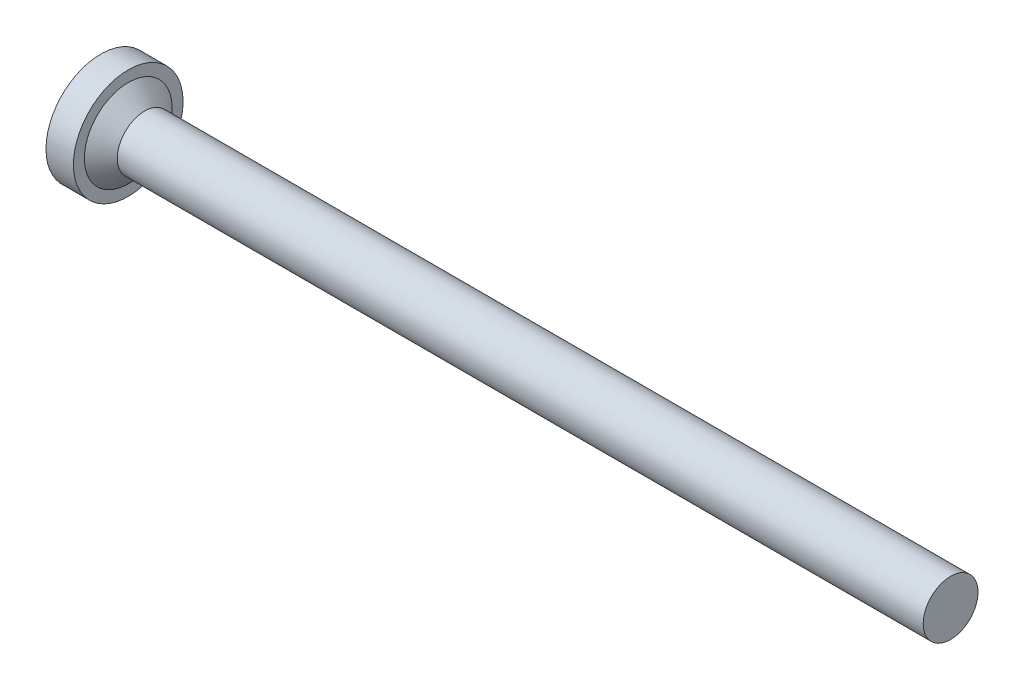
SolidWorks part; units mm, degrees
ref_plane "前视基准面" through (0, 0, 0) normal (0, 0, 1) x (1, 0, 0)
ref_plane "上视基准面" through (0, 0, 0) normal (0, 1, 0) x (1, 0, 0)
ref_plane "右视基准面" through (0, 0, 0) normal (1, 0, 0) x (0, 0, -1)
sketch "草图1" plane through (0, 0, 0) normal (1, 0, 0) x (0, 0, -1)
  circle A0 centre (0, 0) radius 5
  dimension "D1" = 10
extrude "凸台-拉伸1" add sketch "草图1" along normal blind 150
sketch "草图2" plane through (0, 0, 0) normal (-1, 0, 0) x (0, 0, 1)
  circle A0 centre (0, 0) radius 10
  dimension "D1" = 20
extrude "凸台-拉伸2" add sketch "草图2" along normal blind 5
chamfer "倒角1" distance 3 angle 45 1 edges at (0, 0, -5)
